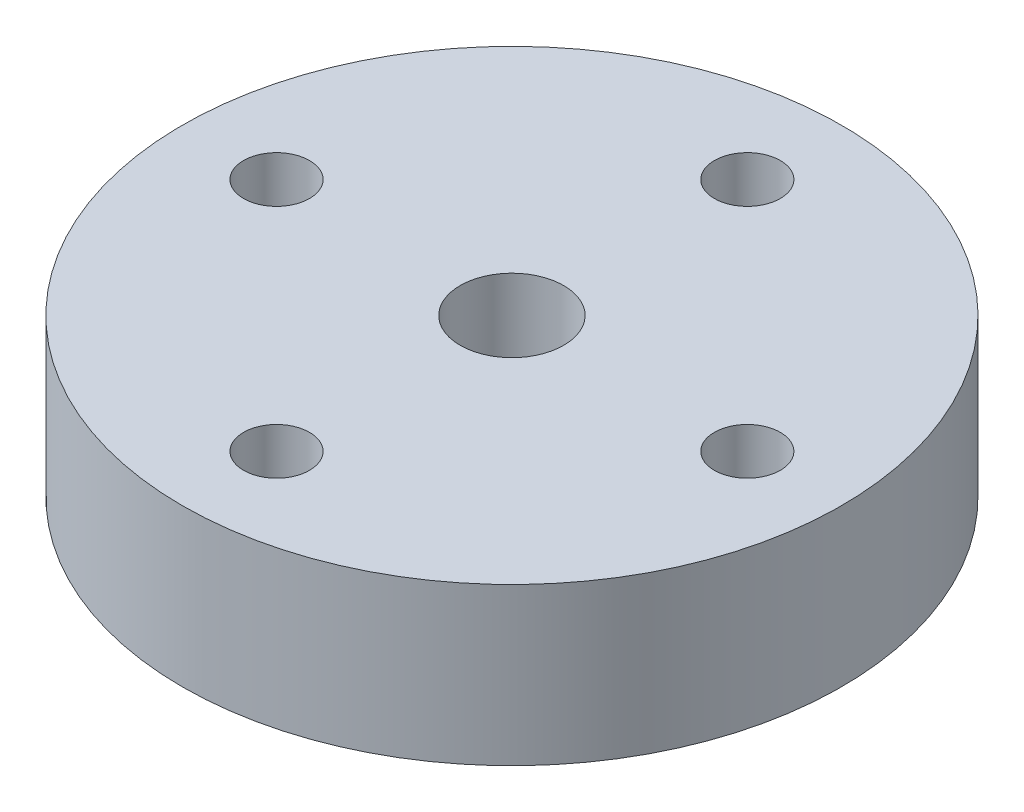
SolidWorks part; units mm, degrees
ref_plane "Front Plane" through (0, 0, 0) normal (0, 0, 1) x (1, 0, 0)
ref_plane "Top Plane" through (0, 0, 0) normal (0, 1, 0) x (1, 0, 0)
ref_plane "Right Plane" through (0, 0, 0) normal (1, 0, 0) x (0, 0, -1)
sketch "Sketch1" plane through (0, 0, 0) normal (0, 1, 0) x (1, 0, 0)
  line L0 (0, 7.5) -> (0, -7.5) construction
  line L1 (-7.5, 0) -> (7.5, 0) construction
  circle A0 centre (0, 0) radius 10.5
  circle A1 centre (0, 0) radius 1.65
  circle A2 centre (-7.5, 0) radius 1.05
  circle A3 centre (0, 7.5) radius 1.05
  circle A4 centre (7.5, 0) radius 1.05
  circle A5 centre (0, -7.5) radius 1.05
  point P7 (0, 0)
  point P10 (0, 0)
  dimension "D1" = 21
  dimension "D2" = 3.3
  dimension "D5" = 2.1
  dimension "D3" = 15
  dimension "D4" = 15
extrude "Boss-Extrude1" add sketch "Sketch1" along normal blind 5
